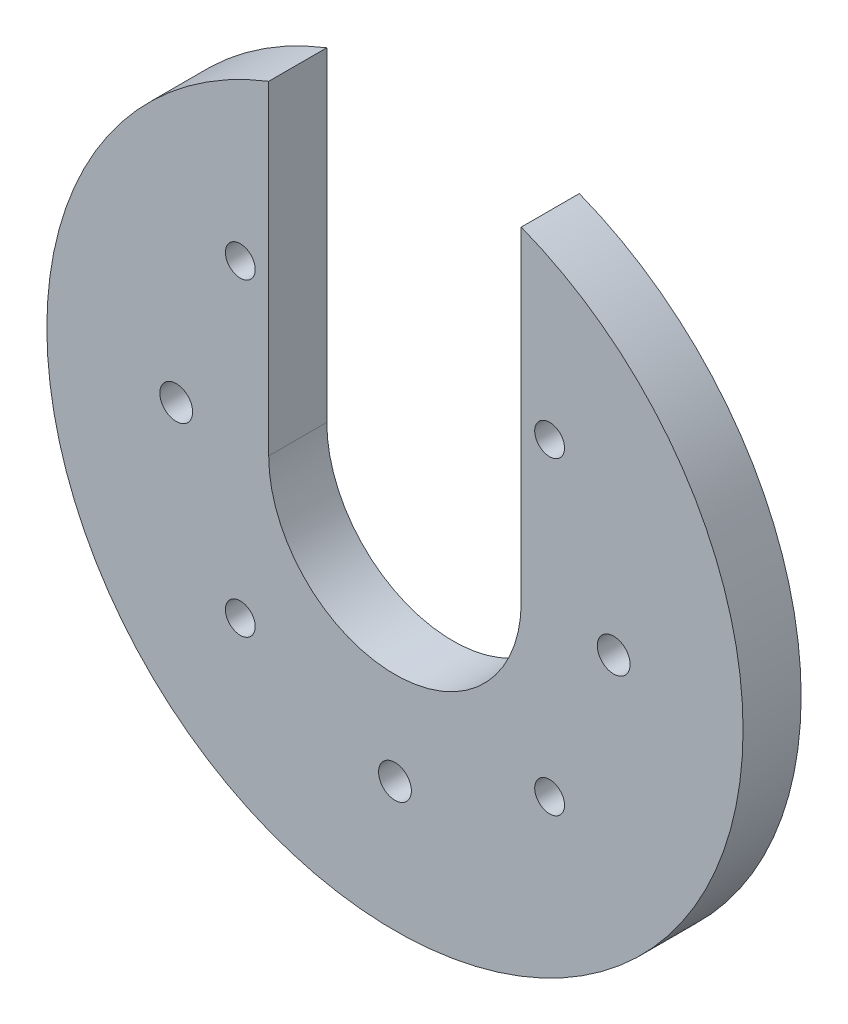
SolidWorks part; units mm, degrees
material "Beech"
ref_plane "Front Plane" through (0, 0, 0) normal (0, 0, 1) x (1, 0, 0)
ref_plane "Top Plane" through (0, 0, 0) normal (0, 1, 0) x (1, 0, 0)
ref_plane "Right Plane" through (0, 0, 0) normal (1, 0, 0) x (0, 0, -1)
sketch "Sketch1" plane through (0, 0, 0) normal (0, 0, 1) x (1, 0, 0)
  line L0 (0, 35.0139) -> (0, -35.0139) construction
  line L1 (-35.0139, 0) -> (35.0139, 0) construction
  line L2 (12.7, 0) -> (22, 0) construction
  line L4 (-12.7, 0) -> (-12.7, 32.6295)
  line L5 (12.7, 0) -> (12.7, 32.6295)
  arc A0 (-12.7, 32.6295) -> (12.7, 32.6295) centre (0, 0) ccw
  arc A1 (-12.7, 0) -> (12.7, 0) centre (0, 0) ccw
  circle A2 centre (22, 0) radius 1.65
  circle A3 centre (0, -22) radius 1.65
  circle A4 centre (-22, 0) radius 1.65
  circle A5 centre (0, 22) radius 1.65 [skipped]
  point P20 (0, 0)
  point P29 (0, 0)
  dimension "D1" = 70.0278
  dimension "D2" = 25.4
  dimension "D4" = 3.3
  dimension "D3" = 22
  dimension "D5" = 4
extrude "Boss-Extrude1" add sketch "Sketch1" along normal blind 5.842
sketch "Sketch2" plane through (0, 0, 5.842) normal (0, 0, 1) x (1, 0, 0)
  line L0 (-15.5563, -15.5563) -> (0, 0) construction
  line L1 (0, 0) -> (0, -22) construction
  circle A0 centre (-15.5563, -15.5563) radius 1.5
  circle A1 centre (-15.5563, 15.5563) radius 1.5
  circle A2 centre (15.5563, 15.5563) radius 1.5
  circle A3 centre (15.5563, -15.5563) radius 1.5
  point P15 (0, 0)
  dimension "D2" = 3
  dimension "D3" = 4
  dimension "D1" = 45
extrude "Cut-Extrude1" cut sketch "Sketch2" against normal through all
